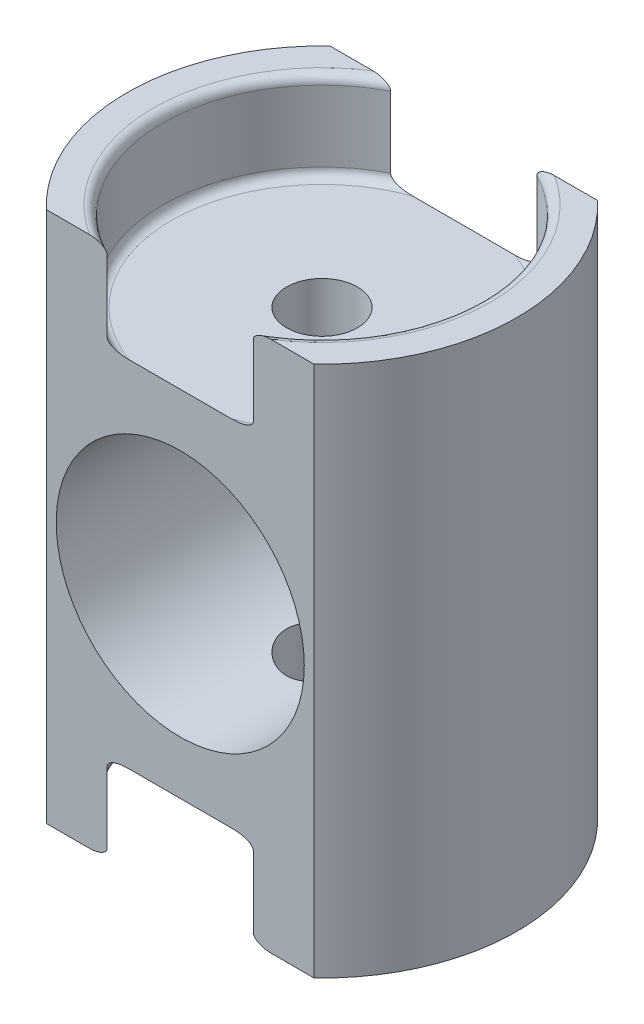
SolidWorks part; units mm, degrees
ref_plane "Face" through (0, 0, 0) normal (0, 0, 1) x (1, 0, 0)
ref_plane "Dessus" through (0, 0, 0) normal (0, 1, 0) x (1, 0, 0)
ref_plane "Droite" through (0, 0, 0) normal (1, 0, 0) x (0, 0, -1)
sketch "Esquisse1" plane through (0, 0, 0) normal (0, 0, 1) x (1, 0, 0)
  line L0 (0, 0) -> (0, -26) construction
  line L1 (0, 0) -> (19, 0) construction
  line L2 (-2, 10) -> (-8.5, 10)
  line L3 (-9, 10.5) -> (-9, 14.5)
  line L4 (-9.5, 15) -> (-11, 15)
  line L5 (-11, 15) -> (-11, -15)
  line L6 (-2, 10) -> (-2, -10)
  line L8 (-9.5, -15) -> (-11, -15)
  line L9 (-9, -10.5) -> (-9, -14.5)
  line L10 (-2, -10) -> (-8.5, -10)
  arc A0 (-9, 14.5) -> (-9.5, 15) centre (-9.5, 14.5) ccw
  arc A1 (-9, -14.5) -> (-9.5, -15) centre (-9.5, -14.5) cw
  arc A2 (-8.5, 10) -> (-9, 10.5) centre (-8.5, 10.5) cw
  arc A3 (-8.5, -10) -> (-9, -10.5) centre (-8.5, -10.5) ccw
  point P14 (-9, 15)
  point P17 (-9, -15)
  point P20 (-9, 10)
  point P23 (-9, -10)
  dimension "D6" = 0.5
  dimension "D1" = 20
  dimension "D2" = 30
  dimension "D3" = 2
  dimension "D4" = 9
  dimension "D5" = 11
revolve "Base-Révolution" add sketch "Esquisse1" angle 360 about L0
sketch "Esquisse2" plane through (-15, 15, 0) normal (0, -1, 0) x (0, 0, -1)
  line L2 (8, 27.7664) -> (8, -4.2336)
  line L3 (-12, 27.7664) -> (-8, 27.7664)
  line L4 (-12, 27.7664) -> (-12, -4.2336)
  line L5 (-12, -4.2336) -> (-8, -4.2336)
  line L6 (-8, 27.7664) -> (-8, -4.2336)
  line L7 (12, -4.2336) -> (8, -4.2336)
  line L8 (12, 27.7664) -> (12, -4.2336)
  line L9 (12, 27.7664) -> (8, 27.7664)
  dimension "D1" = 8
  dimension "D2" = 8
extrude "Enlèv. mat.-Extru.1" cut sketch "Esquisse2" along normal through all
sketch "Esquisse3" plane through (0, 0, 8) normal (0, 0, 1) x (1, 0, 0)
  circle A0 centre (0, 0) radius 7
  dimension "D1" = 14
extrude "Enlèv. mat.-Extru.2" cut sketch "Esquisse3" against normal through all
